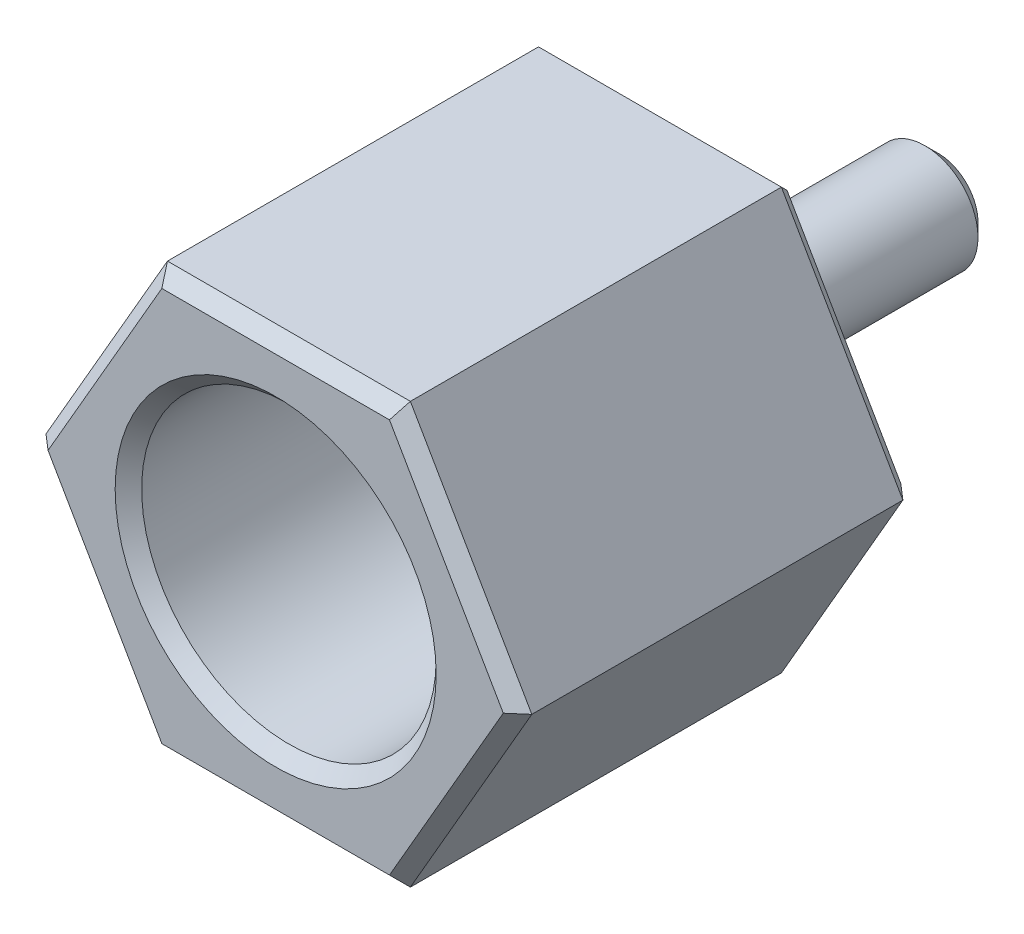
SolidWorks part; units mm, degrees
material "Brass"
ref_plane "Ground_Plane" through (0, 0, 0) normal (0, 0, 1) x (1, 0, 0)
ref_plane "VehicleCentre_Plane" through (0, 0, 0) normal (0, 1, 0) x (1, 0, 0)
ref_plane "FrontAxle_Plane" through (0, 0, 0) normal (1, 0, 0) x (0, 0, -1)
sketch "Sketch1" plane through (0, 0, 0) normal (0, 1, 0) x (1, 0, 0)
  line L0 (1, 25) -> (2, 25)
  line L1 (2, 25) -> (2, 15)
  line L2 (2, 15) -> (7.9375, 15)
  line L3 (7.9375, 15) -> (7.9375, 0)
  line L4 (7.9375, 0) -> (5.5562, 0)
  line L5 (5.5562, 0) -> (5.5562, 12)
  line L6 (5.5562, 12) -> (1, 12)
  line L7 (1, 12) -> (1, 25)
  line L8 (0, 0) -> (0, 25) construction
  point P11 (3.2781, 12)
  point P12 (0, 0)
  dimension "D1" = 25
  dimension "D2" = 7.9375
  dimension "D3" = 5.5562
  dimension "D4" = 3
  dimension "D5" = 15
  dimension "D6" = 1
  dimension "D7" = 2
revolve "Revolve1" add sketch "Sketch1" angle 360 about L8
sketch "Sketch2" plane through (0, 0, -15) normal (0, 0, -1) x (-1, 0, 0)
  line L1 (9.1654, 0) -> (4.5827, 7.9375)
  line L2 (4.5827, 7.9375) -> (-4.5827, 7.9375)
  line L3 (-4.5827, 7.9375) -> (-9.1654, 0)
  line L4 (-9.1654, 0) -> (-4.5827, -7.9375)
  line L5 (-4.5827, -7.9375) -> (4.5827, -7.9375)
  line L6 (4.5827, -7.9375) -> (9.1654, 0)
  circle A0 centre (0, 0) radius 7.9375 construction
  circle A2 centre (0, 0) radius 7.9375 construction
  circle A5 centre (0, 0) radius 5.5562 construction
  circle A6 centre (0, 0) radius 5.5562
  point P13 (0, 0)
  point P14 (0, 0)
extrude "Boss-Extrude1" add sketch "Sketch2" against normal through all
chamfer "Chamfer1" distance 0.5 angle 45 14 edges at (5.5562, 0, 0) (6.8741, -3.9688, -15) (6.8741, -3.9688, 0) (0, -7.9375, -15) (0, -7.9375, 0) (-6.8741, -3.9687, -15) (-6.8741, -3.9687, 0) (-6.8741, 3.9688, -15) (-6.8741, 3.9688, 0) (0, 7.9375, -15) (0, 7.9375, 0) (6.8741, 3.9687, -15) (6.8741, 3.9687, 0) (2, 0, -25)
